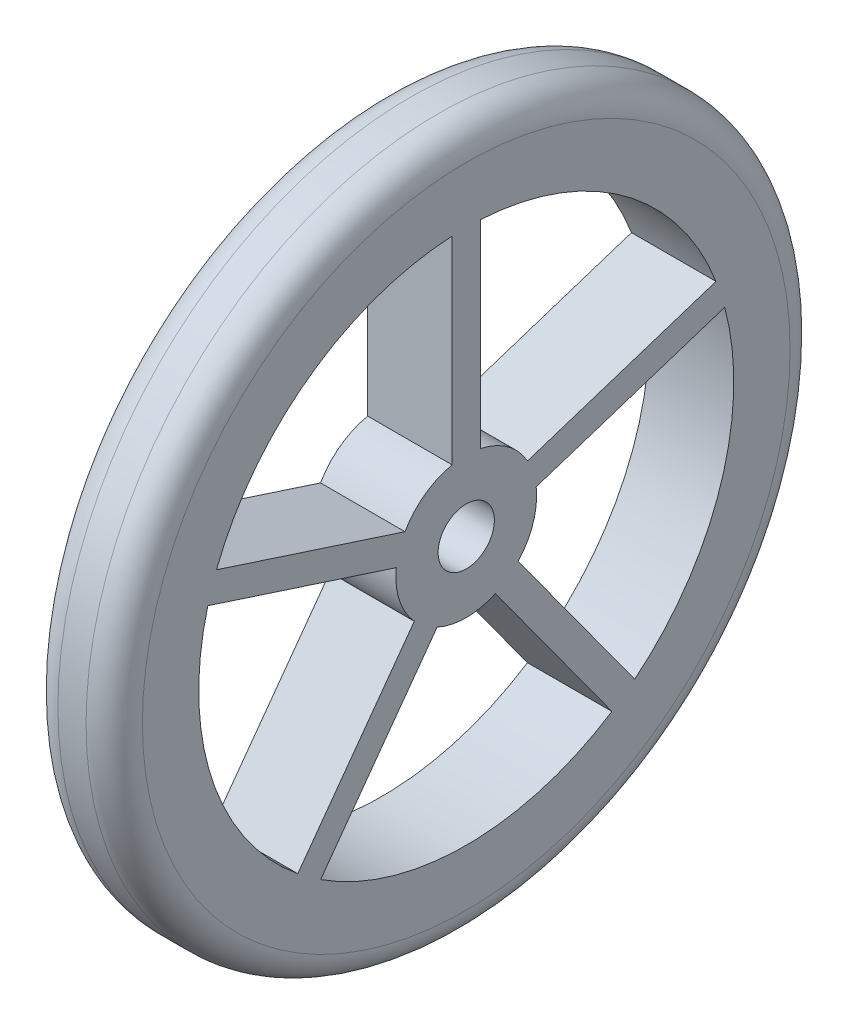
SolidWorks part; units mm, degrees
ref_plane "Front Plane" through (0, 0, 0) normal (0, 0, 1) x (1, 0, 0)
ref_plane "Top Plane" through (0, 0, 0) normal (0, 1, 0) x (1, 0, 0)
ref_plane "Right Plane" through (0, 0, 0) normal (1, 0, 0) x (0, 0, -1)
sketch "Sketch1" plane through (0, 0, 0) normal (1, 0, 0) x (0, 0, -1)
  line L0 (183.5405, 49.1213) -> (49.6822, 5.6281)
  line L2 (-10, 189.7367) -> (-10, 48.9898)
  line L4 (10, 189.7367) -> (10, 48.9898)
  line L5 (177.3601, 68.1424) -> (43.5019, 24.6492)
  line L6 (103.4342, -159.378) -> (20.7053, -45.5114)
  line L7 (119.6146, -147.6223) -> (36.8856, -33.7557)
  line L8 (-119.6146, -147.6223) -> (-36.8856, -33.7557)
  line L9 (-103.4342, -159.378) -> (-20.7053, -45.5114)
  line L10 (-177.3601, 68.1424) -> (-43.5019, 24.6492)
  line L11 (-183.5405, 49.1213) -> (-49.6822, 5.6281)
  circle A0 centre (0, 0) radius 20
  arc A1 (43.5019, 24.6492) -> (10, 48.9898) centre (0, 0) ccw
  arc A2 (-10, 189.7367) -> (-177.3601, 68.1424) centre (0, 0) ccw
  circle A3 centre (0, 0) radius 250
  arc A4 (177.3601, 68.1424) -> (10, 189.7367) centre (0, 0) ccw
  arc A5 (-10, 48.9898) -> (-43.5019, 24.6492) centre (0, 0) ccw
  arc A6 (-49.6822, 5.6281) -> (-36.8856, -33.7557) centre (0, 0) ccw
  arc A7 (-183.5405, 49.1213) -> (-119.6146, -147.6223) centre (0, 0) ccw
  arc A8 (36.8856, -33.7557) -> (49.6822, 5.6281) centre (0, 0) ccw
  arc A9 (-20.7053, -45.5114) -> (20.7053, -45.5114) centre (0, 0) ccw
  arc A10 (-103.4342, -159.378) -> (103.4342, -159.378) centre (0, 0) ccw
  arc A11 (119.6146, -147.6223) -> (183.5405, 49.1213) centre (0, 0) ccw
  point P29 (0, 0)
  dimension "D1" = 500
  dimension "D2" = 380
  dimension "D3" = 100
  dimension "D4" = 40
  dimension "D5" = 5
extrude "Boss-Extrude1" add sketch "Sketch1" along normal blind 60
fillet "Fillet1" radius 20 2 edges at (0, 0, -250) (60, 0, -250)
